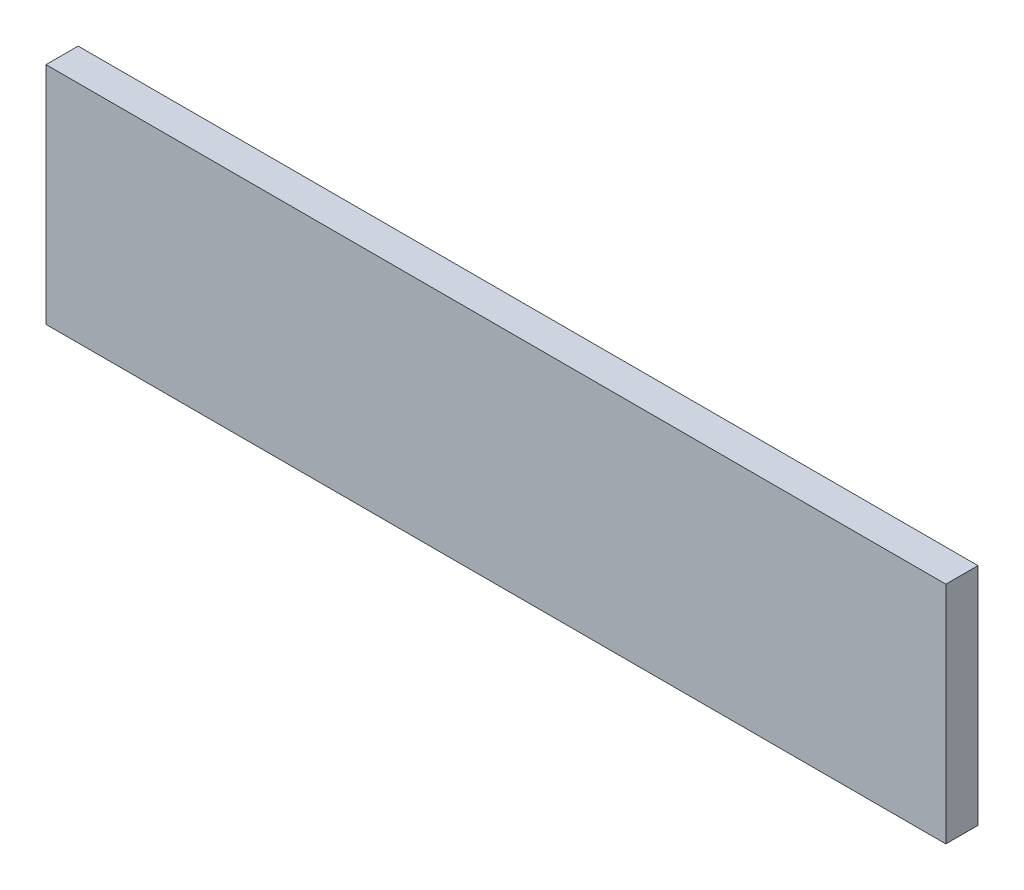
SolidWorks part; units mm, degrees
material "Cedar"
ref_plane "Front Plane" through (0, 0, 0) normal (0, 0, 1) x (1, 0, 0)
ref_plane "Top Plane" through (0, 0, 0) normal (0, 1, 0) x (1, 0, 0)
ref_plane "Right Plane" through (0, 0, 0) normal (1, 0, 0) x (0, 0, -1)
sketch "Sketch1" plane through (0, 0, 0) normal (0, 0, 1) x (1, 0, 0)
  line L0 (-140, -35) -> (140, 35) construction
  line L1 (-140, -35) -> (140, -35)
  line L2 (-140, -35) -> (-140, 35)
  line L3 (-140, 35) -> (140, 35)
  line L4 (140, -35) -> (140, 35)
  line L5 (-140, 35) -> (140, -35) construction
  point P4 (0, 0)
  dimension "D1" = 280
  dimension "D2" = 70
extrude "Boss-Extrude1" add sketch "Sketch1" along normal blind 10
